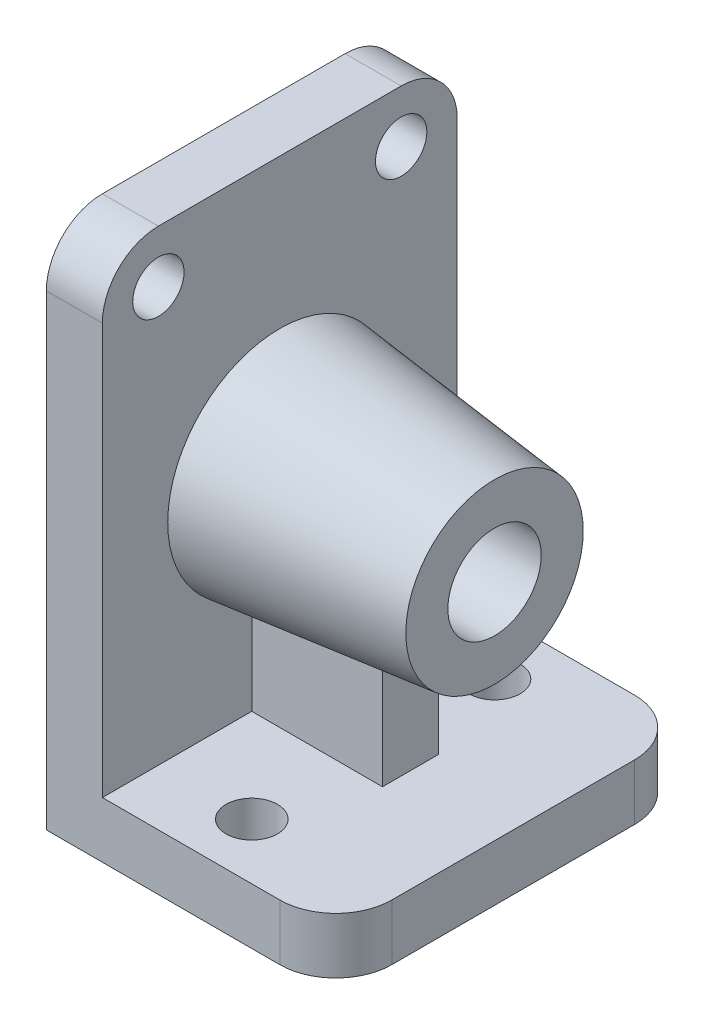
SolidWorks part; units mm, degrees
ref_plane "Front Plane" through (0, 0, 0) normal (0, 0, 1) x (1, 0, 0)
ref_plane "Top Plane" through (0, 0, 0) normal (0, 1, 0) x (1, 0, 0)
ref_plane "Right Plane" through (0, 0, 0) normal (1, 0, 0) x (0, 0, -1)
sketch "Sketch1" plane through (0, 0, 0) normal (0, 0, 1) x (1, 0, 0)
  line L0 (0, 70.9193) -> (0, -41.0807)
  line L1 (0, -41.0807) -> (62, -41.0807)
  line L2 (62, -41.0807) -> (62, -29.0807)
  line L3 (62, -29.0807) -> (12, -29.0807)
  line L4 (12, -29.0807) -> (12, 70.9193)
  line L5 (12, 70.9193) -> (0, 70.9193)
  dimension "D1" = 112
  dimension "D3" = 50
  dimension "D4" = 12
extrude "Boss-Extrude1" add sketch "Sketch1" against normal blind 76
fillet "Fillet1" radius 12 4 edges at (62, -35.0807, -76) (62, -35.0807, 0) (6, 70.9193, -76) (6, 70.9193, 0)
sketch "Sketch5" plane through (0, -29.0807, 0) normal (0, 1, 0) x (1, 0, 0)
  line L0 (12, 76) -> (12, 0) construction
  line L1 (12, 64) -> (12, 12) construction
  line L2 (50, 76) -> (12, 76) construction
  circle A0 centre (32, 12) radius 5.5
  circle A1 centre (32, 64) radius 5.5
  dimension "D1" = 11
  dimension "D2" = 11
  dimension "D3" = 20
  dimension "D4" = 20
  dimension "D5" = 52
  dimension "D6" = 12
extrude "Cut-Extrude1" cut sketch "Sketch5" against normal blind 76
sketch "Sketch6" plane through (12, 0, 0) normal (1, 0, 0) x (0, 0, -1)
  line L0 (76, -29.0807) -> (76, 58.9193) construction
  circle A0 centre (12, 59.6682) radius 5.5
  circle A1 centre (64, 59.6682) radius 5.5
  point P4 (0, 0)
  point P6 (54.8012, 49.6812)
  dimension "D1" = 11
  dimension "D2" = 11
  dimension "D3" = 52
  dimension "D4" = 12
extrude "Cut-Extrude2" cut sketch "Sketch6" against normal blind 76
sketch "Sketch8" plane through (12, 0, 0) normal (1, 0, 0) x (0, 0, -1)
  line L0 (38, 14.9193) -> (38, 38.9193)
  circle A0 centre (38, 14.9193) radius 24
  dimension "D1" = 48
ref_plane "Plane1" through (58, 0, 0) normal (1, 0, 0) x (0, 0, -1)
sketch "Sketch10" plane through (58, 0, 0) normal (1, 0, 0) x (0, 0, -1)
  line L0 (38, 14.9193) -> (38, 33.9193)
  circle A0 centre (38, 14.9193) radius 19
  circle A1 centre (38, 14.9193) radius 10
  dimension "D1" = 38
  dimension "D2" = 20
ref_plane "Plane2" through (0, 0, -38) normal (0, 0, 1) x (1, 0, 0)
sketch "Sketch16" plane through (0, 0, -38) normal (0, 0, 1) x (1, 0, 0)
  line L0 (12, 38.9193) -> (12, 14.9193)
  line L1 (12, 14.9193) -> (12, 38.9193) construction
  line L2 (12, -9.0807) -> (12, 38.9193) construction
  line L3 (58, 33.9193) -> (58, 14.9193)
  line L4 (58, 14.9193) -> (58, 33.9193) construction
  line L5 (58, 14.9193) -> (12, 14.9193)
  line L6 (12, 38.9193) -> (58, 33.9193)
revolve "Revolve1" add sketch "Sketch16" angle 360 about L5
sketch "Sketch17" plane through (58, 0, 0) normal (1, 0, 0) x (0, 0, -1)
  circle A0 centre (38, 14.9193) radius 10
extrude "Cut-Extrude3" cut sketch "Sketch17" against normal blind 46
ref_plane "Plane3" through (40, 0, 0) normal (1, 0, 0) x (0, 0, -1)
sketch "Sketch18" plane through (40, 0, 0) normal (1, 0, 0) x (0, 0, -1)
  line L0 (32, -3.1084) -> (32, -29.0807)
  line L1 (64, -29.0807) -> (12, -29.0807) construction
  line L2 (32, -29.0807) -> (44, -29.0807)
  line L3 (44, -29.0807) -> (44, -3.1084)
  circle A0 centre (38, 14.9193) radius 19 construction
  arc A1 (32, -3.1084) -> (44, -3.1084) centre (38, 14.9193) ccw
  point P6 (38, -29.0807)
  dimension "D1" = 6
extrude "Boss-Extrude3" add sketch "Sketch18" against normal blind 28
